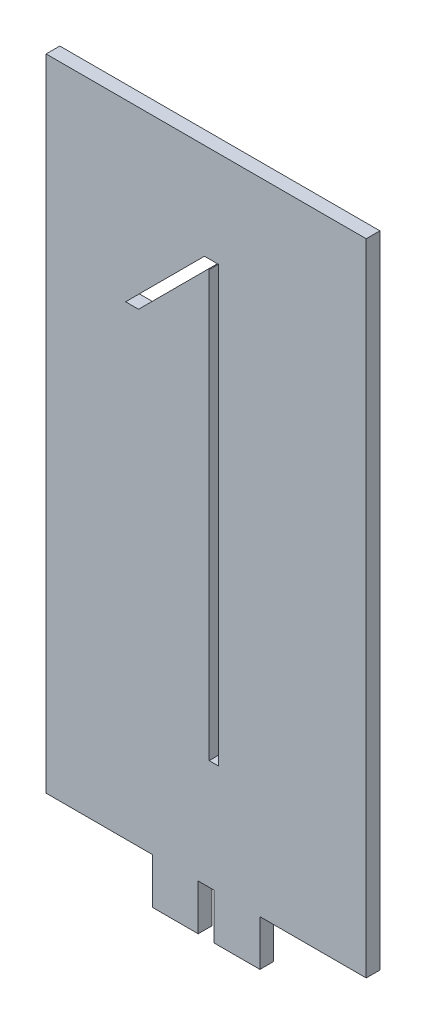
SolidWorks part; units mm, degrees
material "Glas"
ref_plane "Ebene vorne" through (0, 0, 0) normal (0, 0, 1) x (1, 0, 0)
ref_plane "Ebene oben" through (0, 0, 0) normal (0, 1, 0) x (1, 0, 0)
ref_plane "Ebene rechts" through (0, 0, 0) normal (1, 0, 0) x (0, 0, -1)
sketch "Skizze1" plane through (0, 0, 0) normal (0, 0, 1) x (1, 0, 0)
  line L1 (0, 0) -> (35, 0)
  line L2 (0, 0) -> (0, 75)
  line L3 (0, 75) -> (35, 75)
  line L4 (35, 0) -> (35, 75)
  dimension "D1" = 35
  dimension "D2" = 75
extrude "Aufsatz-Linear austragen1" add sketch "Skizze1" along normal blind 1.5
sketch "Skizze2" plane through (0, 0, 1.5) normal (0, 0, 1) x (1, 0, 0)
  line L0 (0, 0) -> (35, 0) construction
  line L1 (0, 0) -> (11.63, 0)
  line L2 (0, 0) -> (0, 5)
  line L3 (0, 5) -> (11.63, 5)
  line L4 (11.63, 0) -> (11.63, 5)
  line L5 (23.38, 5) -> (35, 5)
  line L6 (23.38, 5) -> (23.38, 0)
  line L7 (23.38, 0) -> (35, 0)
  line L8 (35, 5) -> (35, 0)
  line L9 (16.63, 0) -> (18.38, 0)
  line L10 (16.63, 0) -> (16.63, 5)
  line L11 (16.63, 5) -> (18.38, 5)
  line L12 (18.38, 0) -> (18.38, 5)
  dimension "D1" = 5
  dimension "D2" = 5
  dimension "D3" = 5
  dimension "D4" = 11.63
  dimension "D5" = 1.75
  dimension "D6" = 5
extrude "Schnitt-Linear austragen1" cut sketch "Skizze2" against normal blind 1.5
sketch "Skizze6" plane through (0, 0, 1.5) normal (0, 0, 1) x (1, 0, 0)
  line L0 (8.6942, 55.8771) -> (17.3171, 64.5)
  line L1 (17.3171, 64.5) -> (18.8313, 64.5)
  line L2 (18.8313, 64.5) -> (18.8313, 17)
  line L3 (18.8313, 17) -> (17.8313, 17)
  line L4 (17.8313, 17) -> (17.8313, 63.5)
  line L5 (17.8313, 63.5) -> (17.7313, 63.5)
  line L6 (17.7313, 63.5) -> (10.1084, 55.8771)
  line L7 (10.1084, 55.8771) -> (8.6942, 55.8771)
  line L8 (35, 5) -> (23.38, 5) construction
  line L9 (35, 75) -> (0, 75) construction
  dimension "D1" = 1
  dimension "D2" = 1
  dimension "D3" = 1
  dimension "D4" = 0.1
  dimension "D5" = 12
  dimension "D6" = 10.5
extrude "Schnitt-Linear austragen3" cut sketch "Skizze6" against normal blind 1.5
